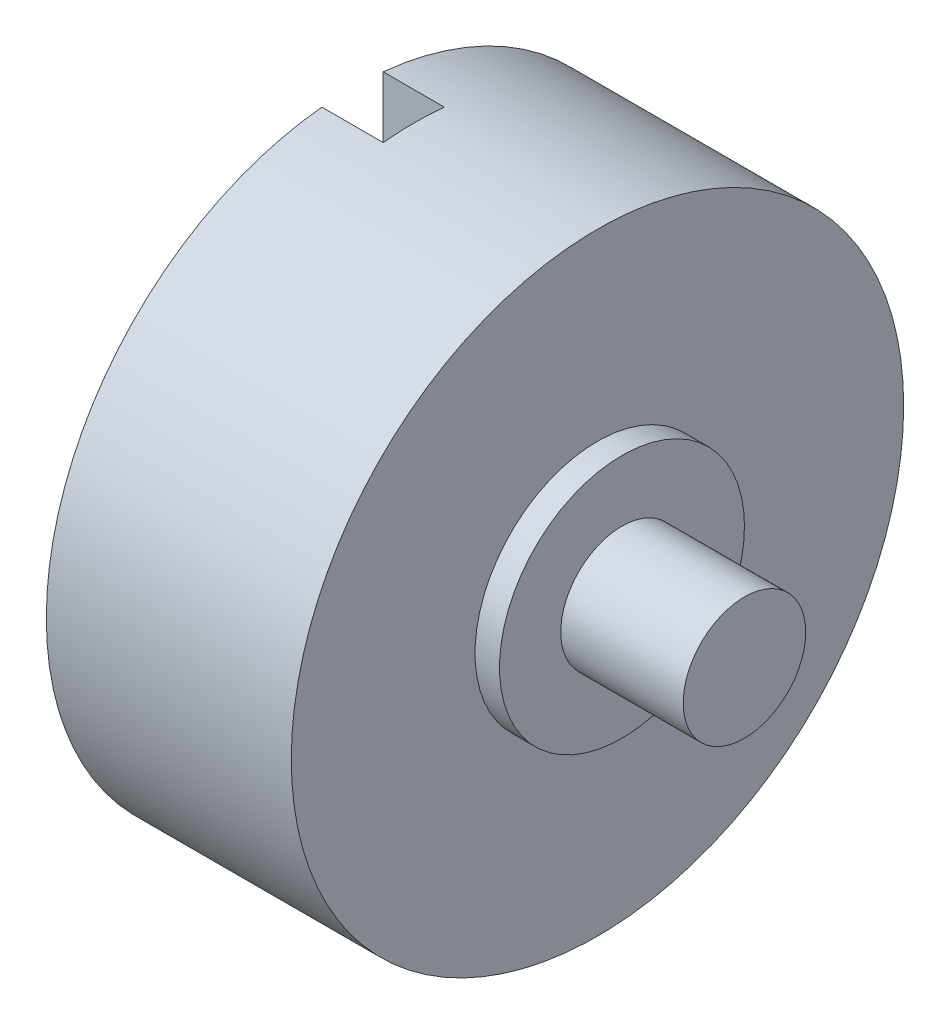
SolidWorks part; units mm, degrees
ref_plane "Front Plane" through (0, 0, 0) normal (0, 0, 1) x (1, 0, 0)
ref_plane "Top Plane" through (0, 0, 0) normal (0, 1, 0) x (1, 0, 0)
ref_plane "Right Plane" through (0, 0, 0) normal (1, 0, 0) x (0, 0, -1)
sketch "Sketch1" plane through (0, 0, 0) normal (1, 0, 0) x (0, 0, -1)
  circle A0 centre (0, 0) radius 25
  dimension "D1" = 50
extrude "Boss-Extrude1" add sketch "Sketch1" along normal mid plane 20
sketch "Sketch2" plane through (10, 0, 0) normal (1, 0, 0) x (0, 0, -1)
  circle A0 centre (0, 0) radius 5
  dimension "D1" = 10
extrude "Boss-Extrude2" add sketch "Sketch2" along normal blind 12
sketch "Sketch3" plane through (-10, 0, 0) normal (-1, 0, 0) x (0, 0, 1)
  line L2 (2.5, 24.8747) -> (2.5, -24.8747)
  line L4 (-2.5, 24.8747) -> (-2.5, -24.8747)
  line L5 (2.2944, 24.8945) -> (-2.2944, -24.8945) construction
  line L6 (2.2944, -24.8945) -> (-2.2944, 24.8945) construction
  circle A0 centre (0, 0) radius 25 construction
  arc A1 (-2.5, -24.8747) -> (2.5, -24.8747) centre (0, 0) ccw
  arc A2 (2.5, 24.8747) -> (-2.5, 24.8747) centre (0, 0) ccw
  point P0 (0, 0)
extrude "Cut-Extrude1" cut sketch "Sketch3" against normal blind 5
sketch "Sketch4" plane through (10, 0, 0) normal (1, 0, 0) x (0, 0, -1)
  circle A0 centre (0, 0) radius 10
  dimension "D1" = 20
extrude "Boss-Extrude3" add sketch "Sketch4" along normal blind 2
